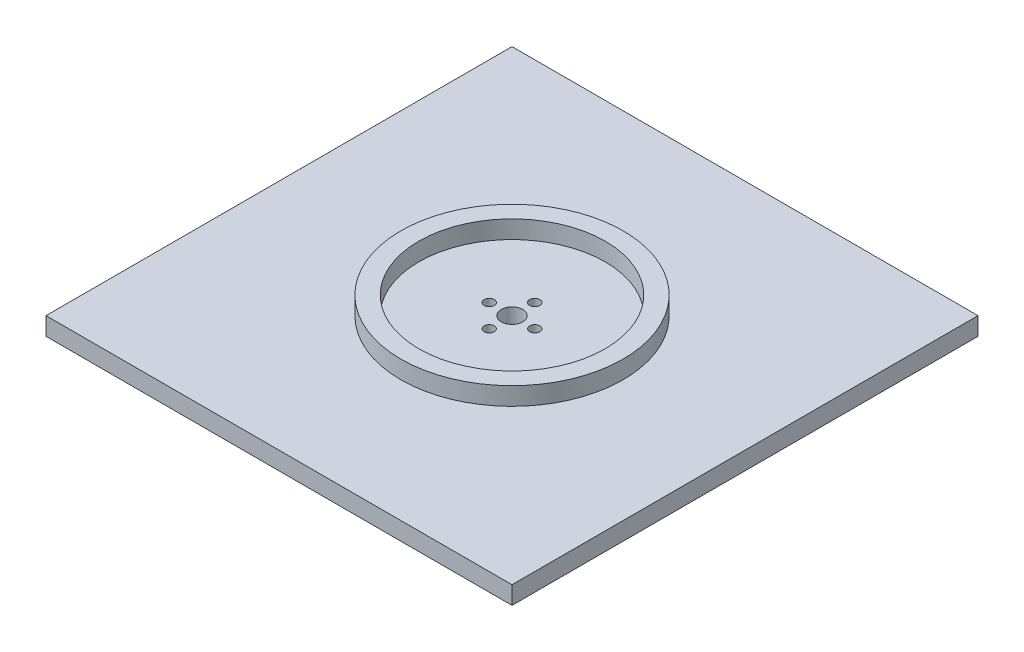
SolidWorks part; units mm, degrees
ref_plane "Front Plane" through (0, 0, 0) normal (0, 0, 1) x (1, 0, 0)
ref_plane "Top Plane" through (0, 0, 0) normal (0, 1, 0) x (1, 0, 0)
ref_plane "Right Plane" through (0, 0, 0) normal (1, 0, 0) x (0, 0, -1)
sketch "Sketch1" plane through (0, 0, 0) normal (0, 1, 0) x (1, 0, 0)
  line L1 (-65, -65) -> (65, -65)
  line L2 (-65, -65) -> (-65, 65)
  line L3 (-65, 65) -> (65, 65)
  line L4 (65, -65) -> (65, 65)
  line L5 (-65, -65) -> (65, 65) construction
  line L6 (-65, 65) -> (65, -65) construction
  circle A0 centre (0, 0) radius 26
  circle A1 centre (0, 0) radius 31
  circle A2 centre (0, 0) radius 24
  dimension "D1" = 52
  dimension "D2" = 62
  dimension "D3" = 48
  dimension "D4" = 130
  dimension "D5" = 130
extrude "Boss-Extrude2" add sketch "Sketch1" along normal blind 5 contours L1 L4 L3 L2 A1 | A1 A0 | A0 A2 | A2
sketch "Sketch2" plane through (0, 5, 0) normal (0, 1, 0) x (1, 0, 0)
  circle A0 centre (0, 0) radius 26
  circle A1 centre (0, 0) radius 31
  dimension "D1" = 52
  dimension "D2" = 62
extrude "Boss-Extrude3" add sketch "Sketch2" along normal blind 5
sketch "Sketch3" plane through (0, 5, 0) normal (0, 1, 0) x (1, 0, 0)
  circle A0 centre (0, 6.35) radius 1.42
  circle A1 centre (6.35, 0) radius 1.42
  circle A2 centre (0, -6.35) radius 1.42
  circle A3 centre (-6.35, 0) radius 1.42
  circle A4 centre (6.35, 0) radius 1.42
  circle A5 centre (0, -6.35) radius 1.42
  circle A6 centre (-6.35, 0) radius 1.42
  circle A7 centre (0, 0) radius 3
  point P12 (0, 0)
  point P19 (0, 0)
  dimension "D1" = 2.84
  dimension "D5" = 6
  dimension "D2" = 6.35
  dimension "D3" = 4
  dimension "D4" = 4
extrude "Cut-Extrude1" cut sketch "Sketch3" against normal blind 5 contours A0 | A1 | A2 | A3 | A7
sketch "Sketch4" plane through (0, 0, 0) normal (0, -1, 0) x (-1, 0, 0)
  circle A0 centre (-6.35, 0) radius 3
  circle A1 centre (0, 6.35) radius 3
  circle A2 centre (6.35, 0) radius 3
  circle A3 centre (0, -6.35) radius 3
  point P12 (0, 0)
  dimension "D1" = 6
  dimension "D2" = 4
extrude "Cut-Extrude2" cut sketch "Sketch4" against normal blind 3
